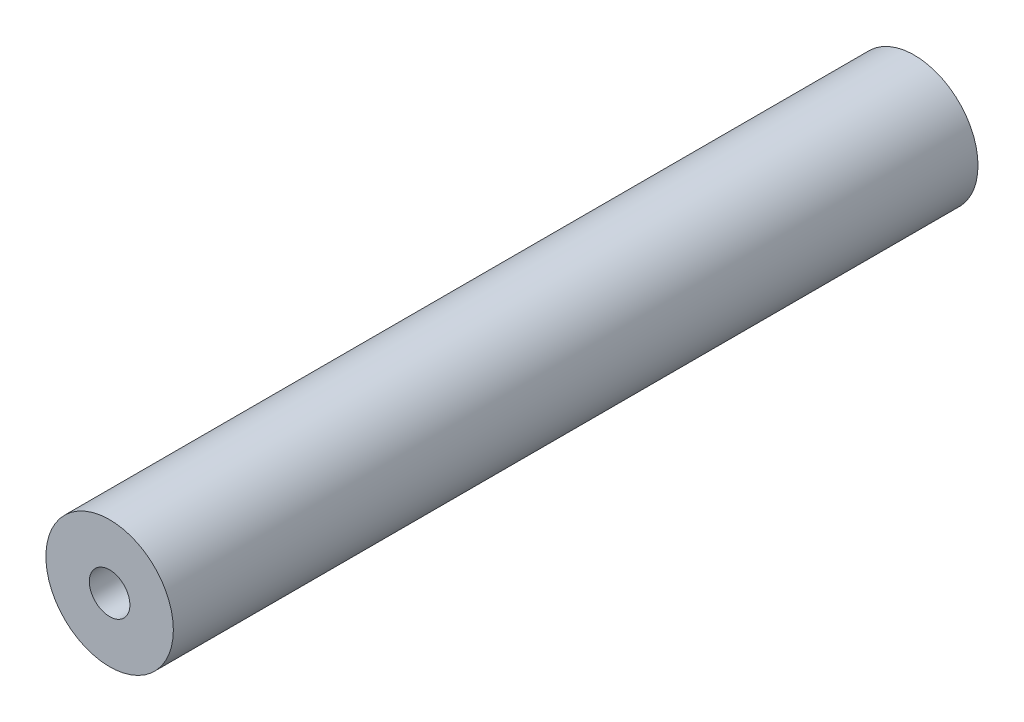
SolidWorks part; units mm, degrees
material "6061-T6 (SS)"
ref_plane "Front Plane" through (0, 0, 0) normal (0, 0, 1) x (1, 0, 0)
ref_plane "Top Plane" through (0, 0, 0) normal (0, 1, 0) x (1, 0, 0)
ref_plane "Right Plane" through (0, 0, 0) normal (1, 0, 0) x (0, 0, -1)
sketch "Sketch1" plane through (0, 0, 0) normal (0, 0, 1) x (1, 0, 0)
  circle A1 centre (0, 0) radius 6.35
  dimension "D2" = 12.7
extrude "Boss-Extrude1" add sketch "Sketch1" along normal mid plane 80.17
hole_wizard "#10-32 Tapped Hole1" positions "3DSketch1" profile "Sketch2" tap size "#10-32" standard "ANSI Inch"
sketch3d "3DSketch1"
  line L0 (0, 0, 40.085) -> (0, 0, -40.085) construction
  point P0 (0, 0, -40.085)
  point P4 (0, 0, 40.085)
sketch "Sketch2" plane through (0, 0, -40.085) normal (1, 0, 0) x (0, 1, 0)
  line L0 (0, 0) -> (0, 13.2428)
  line L1 (0, 13.2428) -> (2.0193, 12.0294)
  line L2 (2.0193, 12.0294) -> (2.0193, 0)
  line L5 (2.0193, 0) -> (0, 0)
  line L10 (0, 13.2428) -> (-2.0193, 12.0294) construction
  line L11 (0, -6.35) -> (0, 107.95) construction
  dimension "Tap Drill Dia." = 4.0386
  dimension "Tap Drill Depth" = 12.0294
  dimension "Drill Angle" = 118
cosmetic thread "Hole Thread1" parameters "D1"=9.652, "D2"=4.826
cosmetic thread "Hole Thread2" parameters "D1"=9.652, "D2"=4.826
